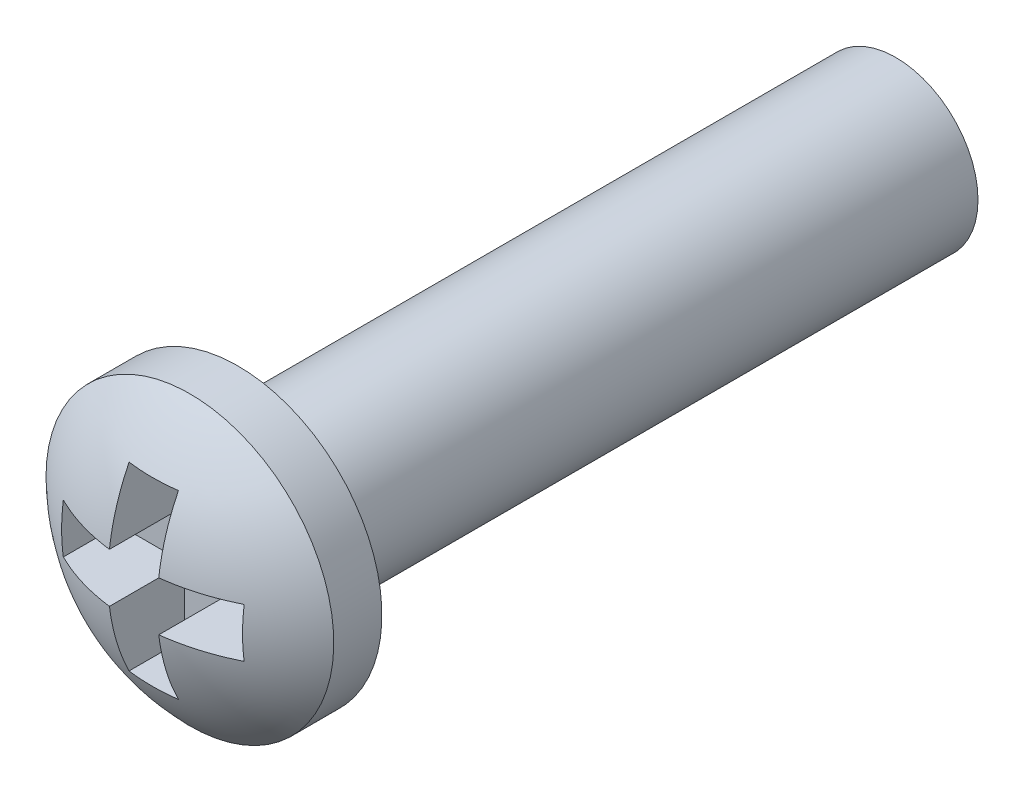
SolidWorks part; units mm, degrees
ref_plane "前视基准面" through (0, 0, 0) normal (0, 0, 1) x (1, 0, 0)
ref_plane "上视基准面" through (0, 0, 0) normal (0, 1, 0) x (1, 0, 0)
ref_plane "右视基准面" through (0, 0, 0) normal (1, 0, 0) x (0, 0, -1)
other "Configuration Table"
sketch "草图1" plane through (0, 0, 0) normal (0, 0, 1) x (1, 0, 0)
  circle A0 centre (0, 0) radius 1
extrude "标准杆径_头下长度" add sketch "草图1" against normal blind 8
sketch "草图2" plane through (0, 0, 0) normal (0, 0, 1) x (1, 0, 0)
  circle A0 centre (0, 0) radius 1.9
sketch "草图4" plane through (0, 0, 0) normal (0, 1, 0) x (1, 0, 0)
  line L0 (0, 0) -> (2.25, 0)
  line L1 (2.25, 0) -> (2.25, -0.1843)
  line L2 (0, -1.2) -> (0, 0)
  line L3 (0, 2) -> (0, -3.2) construction
  arc A0 (2.25, -0.1843) -> (0, -1.2) centre (0, 1.8) cw
sketch "草图5" plane through (0, 0, 0) normal (0, 0, 1) x (1, 0, 0)
  line L0 (-0.3, -1.1) -> (0.3, -1.1)
  line L1 (0.3, -1.1) -> (0.3, -0.3)
  line L2 (0.3, -0.3) -> (1.1, -0.3)
  line L3 (1.1, -0.3) -> (1.1, 0.3)
  line L4 (1.1, 0.3) -> (0.3, 0.3)
  line L5 (0.3, 0.3) -> (0.3, 1.1)
  line L6 (0.3, 1.1) -> (-0.3, 1.1)
  line L7 (-0.3, 1.1) -> (-0.3, 0.3)
  line L8 (-0.3, 0.3) -> (-1.1, 0.3)
  line L9 (-1.1, 0.3) -> (-1.1, -0.3)
  line L10 (-1.1, -0.3) -> (-0.3, -0.3)
  line L11 (-0.3, -0.3) -> (-0.3, -1.1)
sketch "草图6" plane through (0, 0, 0) normal (0, 1, 0) x (1, 0, 0)
  line L0 (0, 0) -> (1.75, 0)
  line L1 (1.75, 0) -> (1.75, -0.5854)
  line L2 (0, -1.3) -> (0, 0)
  line L3 (0, 2) -> (0, -3.3) construction
  arc A0 (1.75, -0.5854) -> (0, -1.3) centre (0, 1.2) cw
revolve "已确认_十字槽盘头" add sketch "草图6" angle 360 about L3
sketch "草图7" plane through (0, 0, 0) normal (0, 0, 1) x (1, 0, 0)
  line L0 (-0.3, -1.1) -> (0.3, -1.1)
  line L1 (0.3, -1.1) -> (0.3, -0.3)
  line L2 (0.3, -0.3) -> (1.1, -0.3)
  line L3 (1.1, -0.3) -> (1.1, 0.3)
  line L4 (1.1, 0.3) -> (0.3, 0.3)
  line L5 (0.3, 0.3) -> (0.3, 1.1)
  line L6 (0.3, 1.1) -> (-0.3, 1.1)
  line L7 (-0.3, 1.1) -> (-0.3, 0.3)
  line L8 (-0.3, 0.3) -> (-1.1, 0.3)
  line L9 (-1.1, 0.3) -> (-1.1, -0.3)
  line L10 (-1.1, -0.3) -> (-0.3, -0.3)
  line L11 (-0.3, -0.3) -> (-0.3, -1.1)
extrude "十字槽_PH1_简化" cut sketch "草图7" against normal blind 0.96 from offset 1.31
